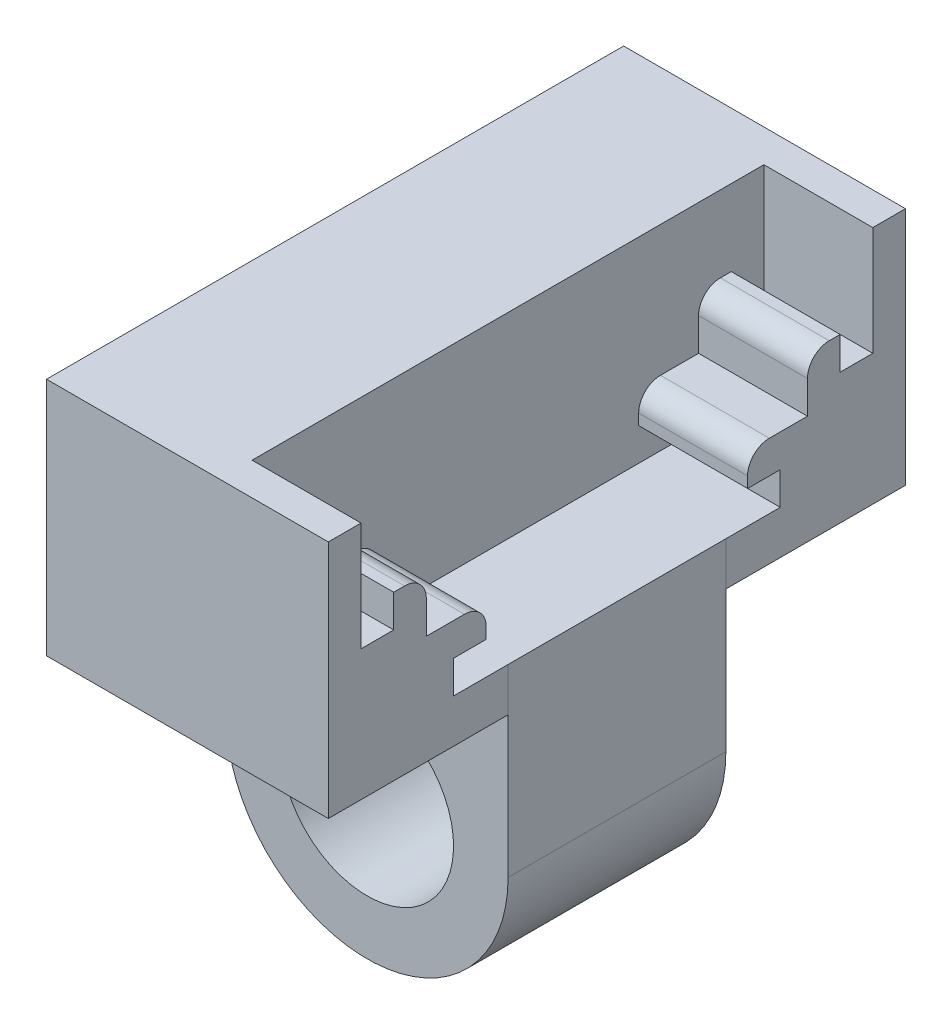
SolidWorks part; units mm, degrees
material "ABS"
ref_plane "Front Plane" through (0, 0, 0) normal (0, 0, 1) x (1, 0, 0)
ref_plane "Top Plane" through (0, 0, 0) normal (0, 1, 0) x (1, 0, 0)
ref_plane "Right Plane" through (0, 0, 0) normal (1, 0, 0) x (0, 0, -1)
sketch "Sketch1" plane through (0, 0, 0) normal (1, 0, 0) x (0, 0, -1)
  line L1 (-26.5, -27.5) -> (-26.5, -5.5)
  line L7 (-23.5, -5.5) -> (-23.5, -15.5)
  line L8 (-23.5, -15.5) -> (-20.5, -15.5)
  line L9 (-20.5, -15.5) -> (-20.5, -12.5)
  line L10 (-20.5, -12.5) -> (-17.5, -12.5)
  line L11 (-17.5, -12.5) -> (-17.5, -17.5)
  line L12 (-17.5, -17.5) -> (-12, -17.5)
  line L14 (-12, -20.5) -> (-15, -20.5)
  line L15 (-15, -20.5) -> (-15, -23.5)
  line L18 (-12, -20.5) -> (-12, -17.5)
  line L19 (0, -27.5) -> (0, -23.5) construction
  line L35 (-23.5, -5.5) -> (-26.5, -5.5)
  line L37 (0, -23.5) -> (0, -27.5) construction
  line L50 (-15, -23.5) -> (0, -23.5)
  line L51 (0, -23.5) -> (0, -27.5)
  line L52 (0, -27.5) -> (-26.5, -27.5)
  dimension "D1" = 3
  dimension "D2" = 3
  dimension "D3" = 3
  dimension "D4" = 20.5
  dimension "D5" = 15
  dimension "D6" = 3
  dimension "D7" = 20.5
  dimension "D8" = 0
  dimension "D9" = 3
  dimension "3" = 3
  dimension "D11" = 10
  dimension "D12" = 3
extrude "Boss-Extrude1" add sketch "Sketch1" along normal blind 10
fillet "Fillet1" radius 2 2 edges at (5, -17.5, 12) (5, -12.5, 17.5)
sketch "Sketch2" plane through (0, 0, 0) normal (-1, 0, 0) x (0, 0, 1)
  line L0 (0, -27.5) -> (0, -23.5) construction
  line L5 (26.5, -5.5) -> (0, -5.5)
  line L6 (26.5, -5.5) -> (26.5, -27.5)
  line L7 (26.5, -27.5) -> (0, -27.5)
  line L8 (0, -5.5) -> (0, -27.5)
extrude "Boss-Extrude2" add sketch "Sketch2" along normal blind 15.88
sketch "Sketch3" plane through (0, 0, 0) normal (0, 0, -1) x (-1, 0, 0)
  line L1 (-10.0057, -40.4332) -> (-10, -23.5)
  line L2 (-10, -23.5) -> (15.88, -23.5)
  line L3 (-10, -27.5) -> (15.88, -27.5) construction
  line L4 (15.88, -5.5) -> (15.88, -27.5) construction
  line L5 (15.88, -23.5) -> (15.8823, -40.4332)
  circle A0 centre (2.9383, -40.4375) radius 7.9375
  arc A1 (-10.0057, -40.4332) -> (15.8823, -40.4332) centre (2.9383, -40.4375) ccw
  dimension "D1" = 15.875
  dimension "D2" = 25.888
  dimension "D3" = 12.9375
extrude "Boss-Extrude3" add sketch "Sketch3" against normal blind 10
mirror "Mirror1" about plane through (10, -23.5, 0) normal (0, 0, 1) of bodies 107
